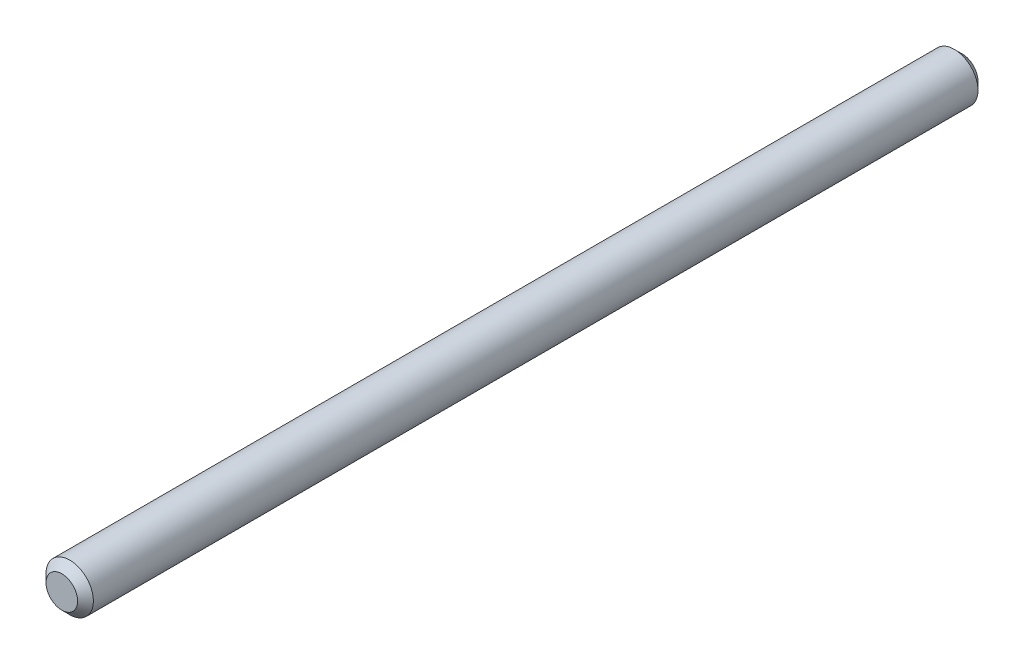
SolidWorks part; units mm, degrees
ref_plane "Front Plane" through (0, 0, 0) normal (0, 0, 1) x (1, 0, 0)
ref_plane "Top Plane" through (0, 0, 0) normal (0, 1, 0) x (1, 0, 0)
ref_plane "Right Plane" through (0, 0, 0) normal (1, 0, 0) x (0, 0, -1)
sketch "Sketch1" plane through (0, 0, 0) normal (0, 0, 1) x (1, 0, 0)
  circle A0 centre (0, 0) radius 3
  dimension "D1" = 6
extrude "Boss-Extrude1" add sketch "Sketch1" along normal blind 114
chamfer "Chamfer1" distance 1 angle 45 2 edges at (3, 0, 114) (3, 0, 0)
equation "\"L\"= 114"
equation "\"D1@Boss-Extrude1\"=\"L\""
